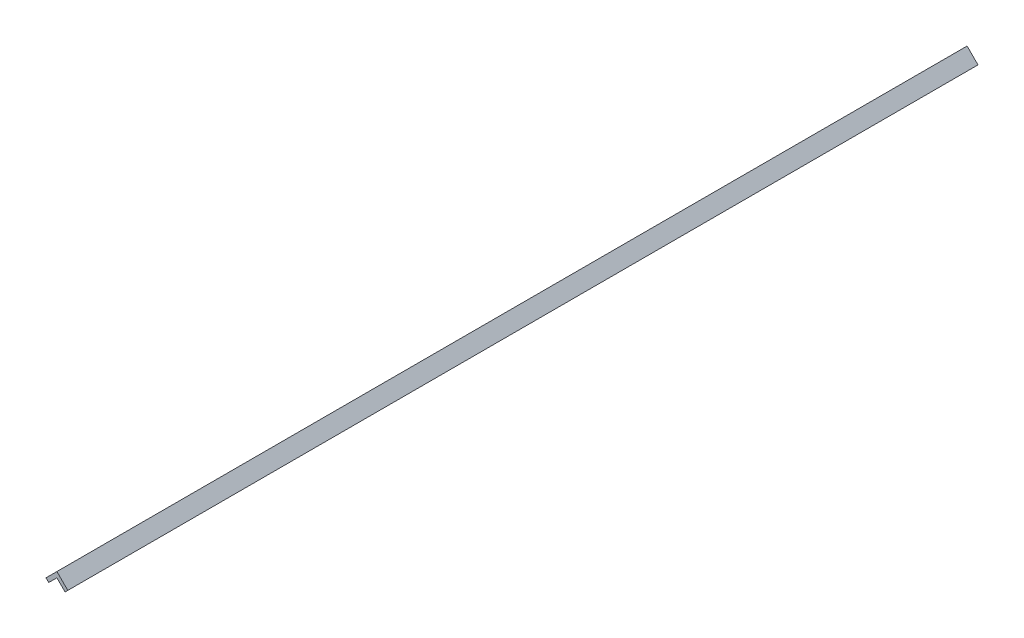
SolidWorks part; units mm, degrees
ref_plane "Plano frontal" through (0, 0, 0) normal (0, 0, 1) x (1, 0, 0)
ref_plane "Plano superior" through (0, 0, 0) normal (0, 1, 0) x (1, 0, 0)
ref_plane "Plano direito" through (0, 0, 0) normal (1, 0, 0) x (0, 0, -1)
sketch "Esboço1" plane through (0, 0, 0) normal (0, 0, 1) x (1, 0, 0)
  line L0 (0, 11.2289) -> (8.9803, 2.2486)
  line L1 (-8.9803, 2.2486) -> (-6.7317, 0)
  line L2 (0, 0) -> (0, 11.2289) construction
  line L3 (-6.7317, 0) -> (0, 6.7317)
  line L4 (8.9803, 2.2486) -> (6.7317, 0)
  line L5 (0, 11.2289) -> (-8.9803, 2.2486)
  line L6 (6.7317, 0) -> (0, 6.7317)
  dimension "D1" = 12.7
  dimension "D2" = 90
  dimension "D3" = 3.18
  dimension "D4" = 6.7317
sketch "Esboço2" plane through (0, 0, 0) normal (0, 1, 0) x (1, 0, 0)
  line L0 (0, -750) -> (0, 750)
  line L1 (0, 0) -> (-59.1058, 0) construction
  point P10 (200, 0)
  dimension "D2" = 750
sweep "Varredura1" add profiles "Esboço1" path "Esboço2"
